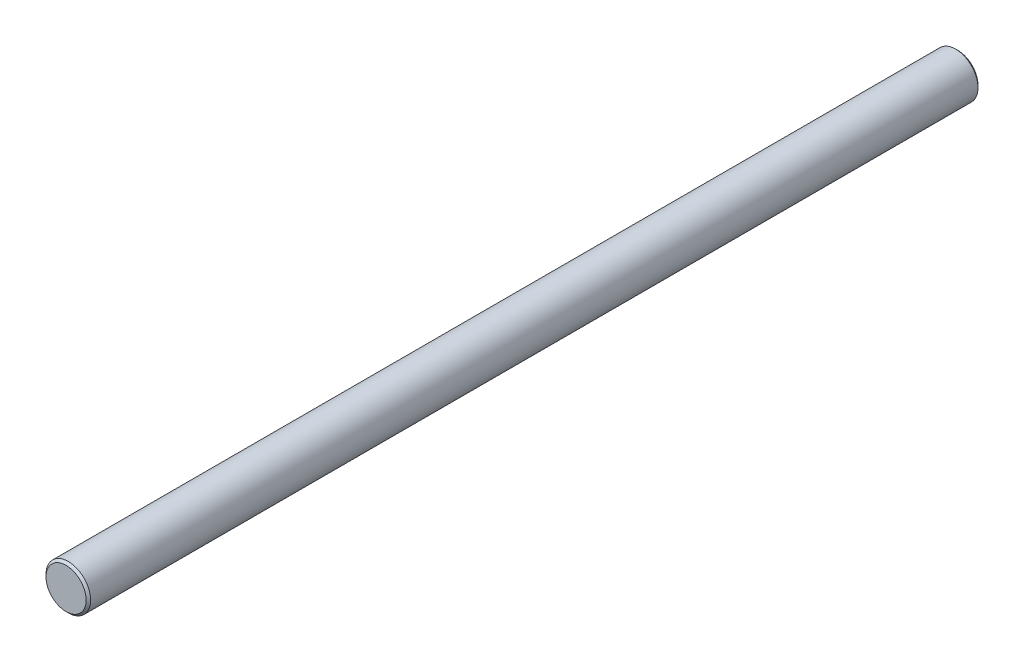
SolidWorks part; units mm, degrees
ref_plane "前视基准面" through (0, 0, 0) normal (0, 0, 1) x (1, 0, 0)
ref_plane "上视基准面" through (0, 0, 0) normal (0, 1, 0) x (1, 0, 0)
ref_plane "右视基准面" through (0, 0, 0) normal (1, 0, 0) x (0, 0, -1)
sketch "草图1" plane through (0, 0, 0) normal (0, 0, 1) x (1, 0, 0)
  circle A0 centre (0, 0) radius 3
  dimension "D1" = 6
extrude "凸台-拉伸1" add sketch "草图1" along normal mid plane 120
chamfer "倒角1" distance 0.3 angle 45 1 edges at (3, 0, 60)
chamfer "倒角2" distance 0.3 angle 45 1 edges at (3, 0, -60)
